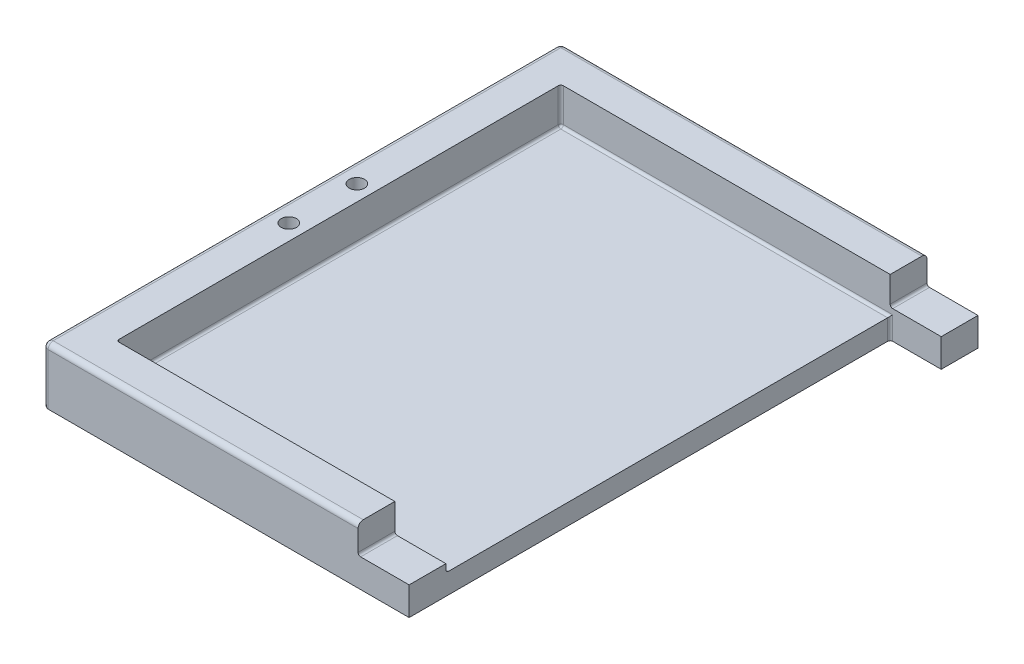
SolidWorks part; units mm, degrees
ref_plane "Front Plane" through (0, 0, 0) normal (0, 0, 1) x (1, 0, 0)
ref_plane "Top Plane" through (0, 0, 0) normal (0, 1, 0) x (1, 0, 0)
ref_plane "Right Plane" through (0, 0, 0) normal (1, 0, 0) x (0, 0, -1)
sketch "Sketch1" plane through (0, 0, 0) normal (0, 1, 0) x (1, 0, 0)
  line L1 (-35.85, 50.7) -> (35.85, 50.7)
  line L2 (-35.85, 50.7) -> (-35.85, -50.7)
  line L3 (-35.85, -50.7) -> (35.85, -50.7)
  line L4 (35.85, 50.7) -> (35.85, -50.7)
  line L5 (-35.85, 50.7) -> (35.85, -50.7) construction
  line L6 (-35.85, -50.7) -> (35.85, 50.7) construction
  point P0 (0, 0)
  dimension "D1" = 71.7
  dimension "D2" = 101.4
extrude "Boss-Extrude1" add sketch "Sketch1" along normal blind 11.1 contours L1 L4 L3 L2
sketch "Sketch5" plane through (35.85, 0, 0) normal (1, 0, 0) x (0, 0, -1)
  line L2 (-43.5, 18.4616) -> (-43.5, 4)
  line L3 (-43.5, 4) -> (43.5, 4)
  line L4 (0, 0) -> (0, 18.4616) construction
  line L5 (50.7, 0) -> (-50.7, 0) construction
  line L7 (-43.5, 18.4616) -> (43.5, 18.4616)
  line L8 (43.5, 18.4616) -> (43.5, 4)
  point P9 (0, 4)
  dimension "D1" = 87
  dimension "D3" = 4
extrude "Cut-Extrude1" cut sketch "Sketch5" against normal blind 64.5
fillet "Fillet2" radius 1 6 edges at (-35.85, 5.55, -50.7) (-35.85, 5.55, 50.7) (0, 11.1, -50.7) (0, 11.1, 50.7) (-35.85, 11.1, 0) (-35.85, 0, 0)
sketch "Sketch7" plane through (0, 11.1, 0) normal (0, 1, 0) x (1, 0, 0)
  line L0 (-35.85, 0) -> (0, 0) construction
  line L1 (-35.85, 50.7) -> (-35.85, -50.7) construction
  line L2 (-34.85, -6.6579) -> (-28.65, -6.6579) construction
  line L3 (-34.85, 49.7) -> (-34.85, -49.7) construction
  circle A0 centre (-31.75, -6.6579) radius 1.5
  circle A1 centre (-31.75, 6.6579) radius 1.5
  dimension "D1" = 3
  dimension "D2" = 6.6579
  dimension "D3" = 6.2
extrude "Cut-Extrude3" cut sketch "Sketch7" against normal blind 4
sketch "Sketch10" plane through (35.85, 0, 0) normal (1, 0, 0) x (0, 0, -1)
  line L1 (50.7, 0) -> (-50.7, 0) construction
  line L7 (-43.5, 11.1) -> (-43.5, 0) construction
  line L8 (-43.5, 11.1) -> (-43.5, 4) construction
  line L9 (-43.5, 5.55) -> (-43.5, 11.1)
  line L10 (-43.5, 11.1) -> (-52.2249, 11.1)
  line L11 (-52.2249, 11.1) -> (-52.2249, 5.55)
  line L12 (-52.2249, 5.55) -> (-43.5, 5.55)
extrude "Cut-Extrude5" cut sketch "Sketch10" against normal blind 10
sketch "Sketch11" plane through (35.85, 0, 0) normal (1, 0, 0) x (0, 0, -1)
  line L0 (43.5, 0) -> (43.5, 11.1) construction
  line L1 (50.7, 0) -> (-50.7, 0) construction
  line L2 (43.5, 4) -> (43.5, 11.1) construction
  line L3 (49.7, 11.1) -> (43.5, 11.1) construction
  line L4 (43.5, 0) -> (50.7, 0)
  line L5 (43.5, 5.55) -> (43.5, 0)
  line L6 (43.5, 5.55) -> (50.7, 5.55)
  line L7 (50.7, 10.1) -> (50.7, 0) construction
  line L8 (50.7, 5.55) -> (50.7, 0)
extrude "Boss-Extrude2" add sketch "Sketch11" along normal blind 10
fillet "Fillet3" radius 0.5 8 edges at (-28.65, 4, 0) (3.6, 4, 43.5) (-28.65, 7.55, -43.5) (-28.65, 7.55, 43.5) (25.85, 5.55, 47.1)
